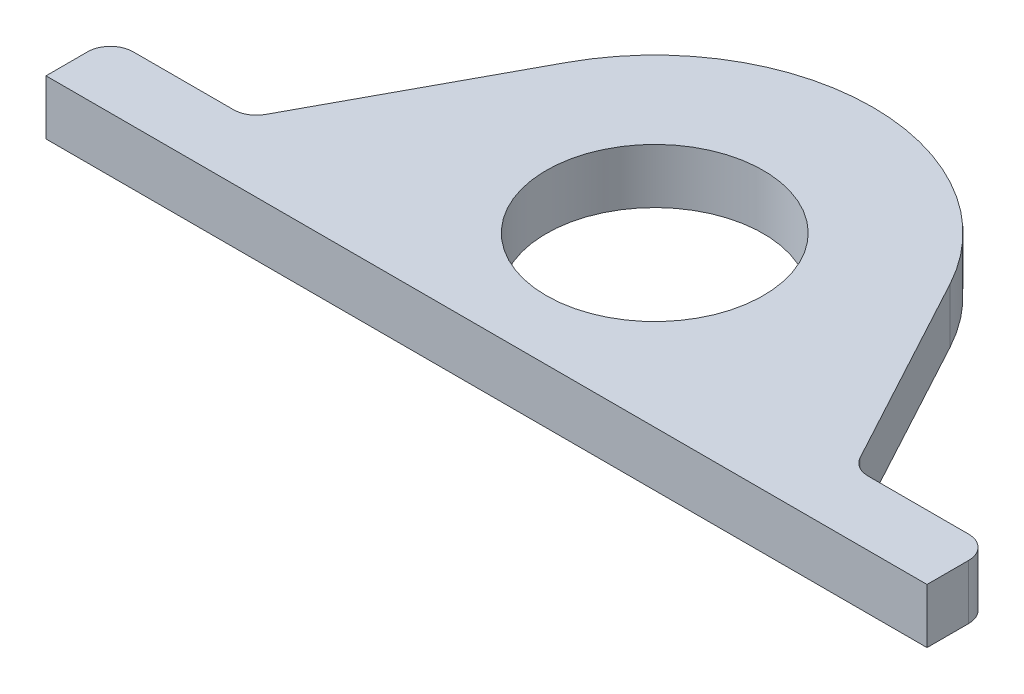
SolidWorks part; units mm, degrees
ref_plane "Front Plane" through (0, 0, 0) normal (0, 0, 1) x (1, 0, 0)
ref_plane "Top Plane" through (0, 0, 0) normal (0, 1, 0) x (1, 0, 0)
ref_plane "Right Plane" through (0, 0, 0) normal (1, 0, 0) x (0, 0, -1)
sketch "Sketch1" plane through (0, 0, 0) normal (0, 1, 0) x (1, 0, 0)
  line L0 (0, 0) -> (0, -23.8) construction
  line L2 (65, -39.8) -> (-65, -39.8)
  line L4 (0, -39.8) -> (0, -23.8) construction
  line L5 (69.5891, -22.7756) -> (91.6057, -22.7756)
  line L6 (-65.1889, -20.15) -> (-42.0661, 22.6998)
  line L7 (42.0661, 22.6998) -> (65.1889, -20.15)
  line L8 (96.6057, -27.7756) -> (96.6057, -39.8)
  line L9 (96.6057, -39.8) -> (65, -39.8)
  line L10 (-96.6057, -27.7756) -> (-96.6057, -39.8)
  line L11 (-69.5891, -22.7756) -> (-91.6057, -22.7756)
  line L12 (-96.6057, -39.8) -> (-65, -39.8)
  circle A0 centre (0, 0) radius 23.8
  arc A1 (42.0661, 22.6998) -> (-42.0661, 22.6998) centre (0, 0) ccw
  arc A2 (91.6057, -22.7756) -> (96.6057, -27.7756) centre (91.6057, -27.7756) cw
  circle A3 centre (0, 0) radius 47.8 construction
  arc A4 (-96.6057, -27.7756) -> (-91.6057, -22.7756) centre (-91.6057, -27.7756) cw
  arc A5 (65.1889, -20.15) -> (69.5891, -22.7756) centre (69.5891, -17.7756) ccw
  arc A6 (-65.1889, -20.15) -> (-69.5891, -22.7756) centre (-69.5891, -17.7756) cw
  point P7 (48, 0)
  point P20 (96.6057, -22.7756)
  point P23 (-96.6057, -22.7756)
  point P26 (66.6057, -22.7756)
  point P29 (-66.6057, -22.7756)
  dimension "D1" = 24
  dimension "D5" = 47.6
  dimension "D7" = 5
  dimension "D2" = 16
  dimension "D3" = 17.1
  dimension "D4" = 130
  dimension "D6" = 30
extrude "Boss-Extrude1" add sketch "Sketch1" along normal blind 12
sketch "Sketch2" plane through (0, 0, 0) normal (0, -1, 0) x (1, 0, 0)
  line L0 (-96.6057, 39.8) -> (96.6057, 39.8) construction
  line L1 (125.5731, 36.9) -> (-142.9656, 36.9)
  line L2 (125.5731, 36.9) -> (125.5731, 93.2555)
  line L3 (125.5731, 93.2555) -> (-142.9656, 93.2555)
  line L4 (-142.9656, 36.9) -> (-142.9656, 93.2555)
  dimension "D1" = 2.9
extrude "Cut-Extrude1" cut sketch "Sketch2" against normal blind 26
